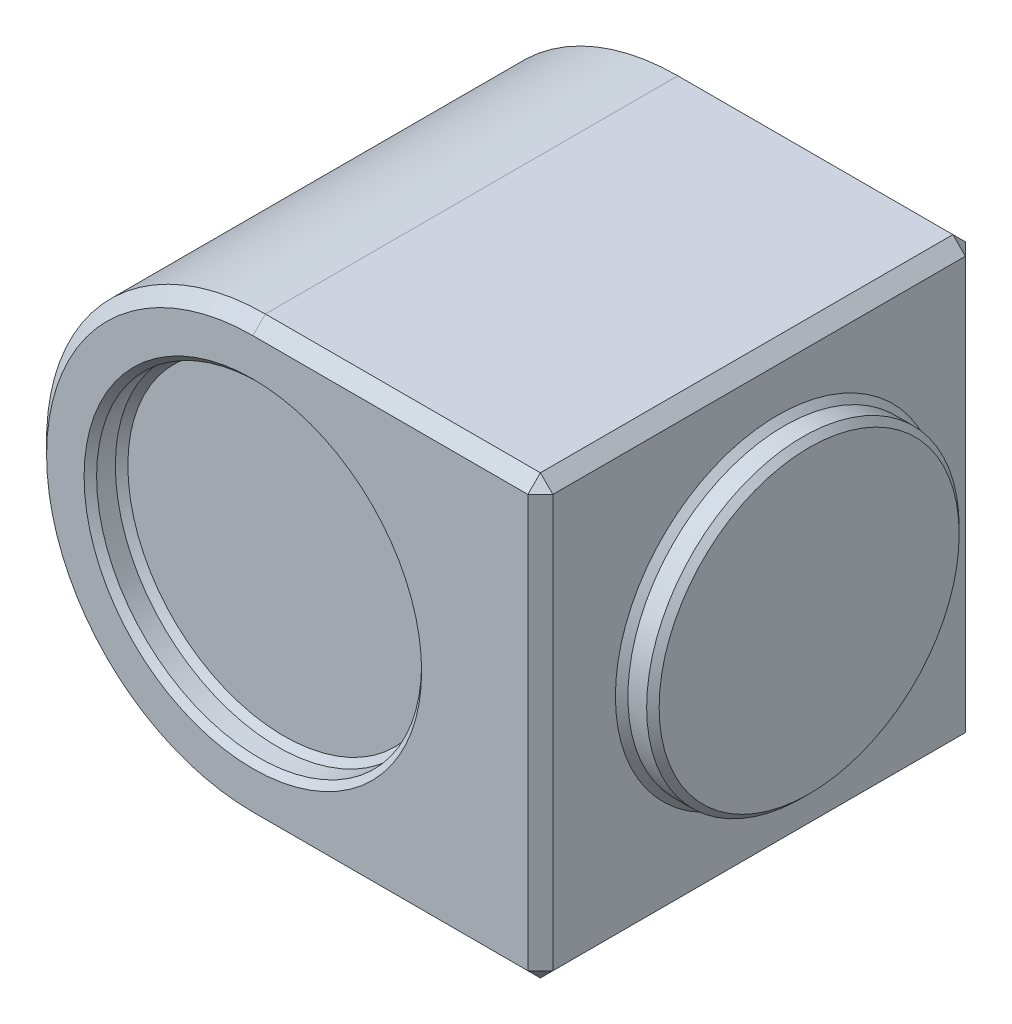
SolidWorks part; units mm, degrees
ref_plane "Front Plane" through (0, 0, 0) normal (0, 0, 1) x (1, 0, 0)
ref_plane "Top Plane" through (0, 0, 0) normal (0, 1, 0) x (1, 0, 0)
ref_plane "Right Plane" through (0, 0, 0) normal (1, 0, 0) x (0, 0, -1)
sketch "Sketch3" plane through (0, 0, 0) normal (0, 0, 1) x (1, 0, 0)
  line L0 (0, 35) -> (46, 35)
  line L1 (46, 35) -> (46, -35)
  line L2 (46, -35) -> (0, -35)
  arc A0 (0, 35) -> (0, -35) centre (0, 0) ccw
  dimension "D1" = 70
  dimension "D2" = 46
extrude "Boss-Extrude1" add sketch "Sketch3" along normal blind 70
sketch "Sketch4" plane through (46, 0, 0) normal (1, 0, 0) x (0, 0, -1)
  line L0 (0, 0) -> (-70, 0) construction
  line L1 (-70, -35) -> (-70, 35) construction
  circle A0 centre (-38, 0) radius 25
  dimension "D1" = 50
  dimension "D2" = 32
extrude "Boss-Extrude2" add sketch "Sketch4" along normal blind 5
sketch "Sketch5" plane through (0, 0, 0) normal (0, 0, -1) x (-1, 0, 0)
  circle A0 centre (0, 0) radius 26
  dimension "D1" = 52
chamfer "Chamfer1" distance 2 angle 45 10 edges at (23, -35, 0) (-35, 0, 0) (23, 35, 0) (46, -35, 35) (46, 0, 0) (46, 35, 35) (23, 35, 70) (46, 0, 70) (23, -35, 70) (-35, 0, 70)
extrude "Cut-Extrude1" cut sketch "Sketch5" against normal blind 5
chamfer "Chamfer3" distance 1 angle 45 4 edges at (-26, 0, 5) (51, 0, 13) (46, 0, 63) (-26, 0, 0)
mirror "Mirror1" about plane through (0, 0, 0) normal (0, 0, 1) of bodies 104
delete or keep bodies "Body-Delete/Keep 1" type delete bodies bodies 104
sketch "Sketch6" plane through (0, 0, 0) normal (0, 1, 0) x (1, 0, 0)
  line L0 (-35, 35) -> (51, 35) construction
  line L1 (-35, 68) -> (-35, 2) construction
  line L2 (51, 14) -> (51, 62) construction
  point P6 (8, 35)
